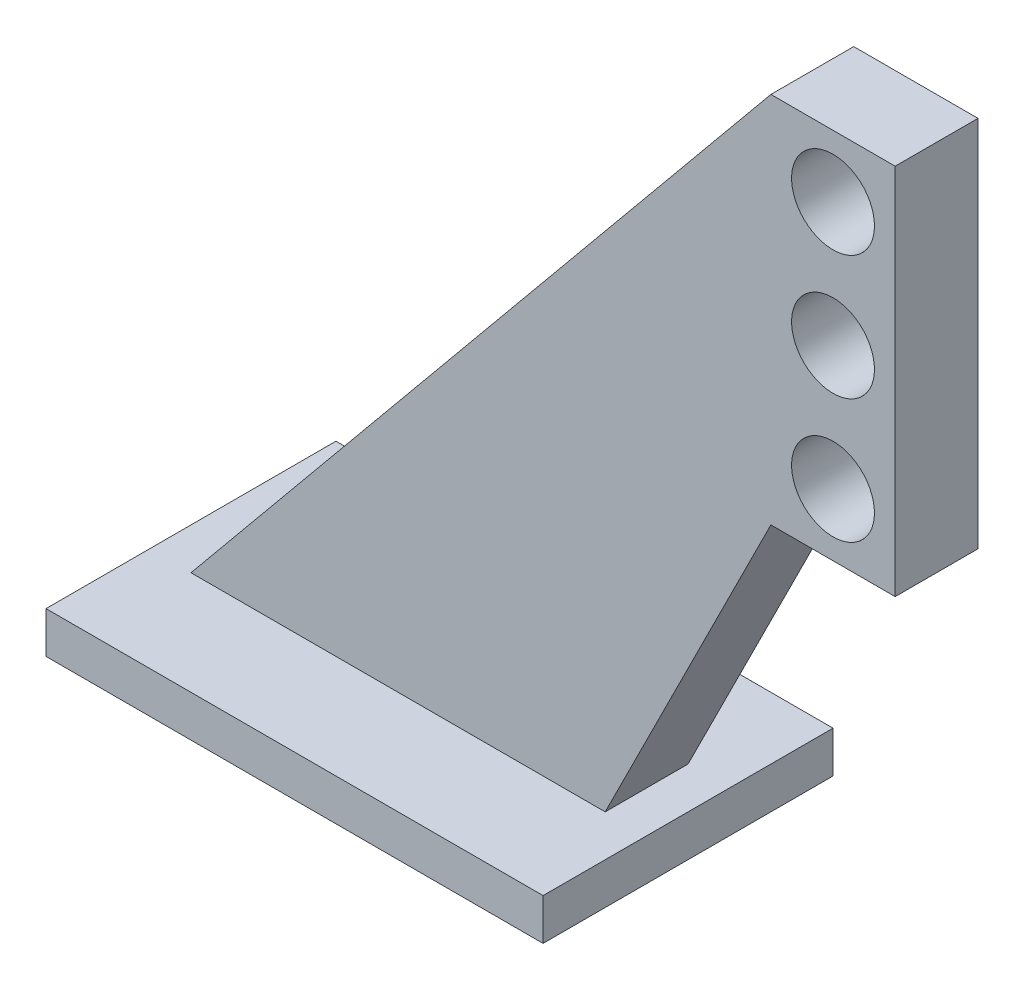
SolidWorks part; units mm, degrees
material "Zero density"
ref_plane "Piano frontale" through (0, 0, 0) normal (0, 0, 1) x (1, 0, 0)
ref_plane "Piano superiore" through (0, 0, 0) normal (0, 1, 0) x (1, 0, 0)
ref_plane "Piano destro" through (0, 0, 0) normal (1, 0, 0) x (0, 0, -1)
sketch "Schizzo1" plane through (0, 0, 0) normal (0, 0, 1) x (1, 0, 0)
  line L0 (0, 0) -> (10, 0)
  line L1 (10, 0) -> (14, 8)
  line L2 (14, 8) -> (17, 8)
  line L3 (17, 8) -> (17, 17)
  line L4 (17, 17) -> (14, 17)
  line L5 (14, 17) -> (0, 0)
  line L6 (15.5, 15.5) -> (15.5, 12.5) construction
  line L7 (15.5, 12.5) -> (15.5, 9.5) construction
  line L8 (15.5, 15.5) -> (17, 17) construction
  line L9 (15.5, 9.5) -> (17, 8) construction
  circle A0 centre (15.5, 15.5) radius 1
  circle A1 centre (15.5, 12.5) radius 1
  circle A2 centre (15.5, 9.5) radius 1
  point P14 (15.5, 17)
  dimension "D7" = 2
  dimension "D1" = 9
  dimension "D2" = 10
  dimension "D3" = 7
  dimension "D4" = 17
  dimension "D5" = 3
  dimension "D6" = 14
  dimension "D8" = 1.5
extrude "Estrusione-Estrusione1" add sketch "Schizzo1" along normal blind 2
sketch "Schizzo2" plane through (0, 0, 0) normal (0, -1, 0) x (1, 0, 0)
  line L0 (0, 2) -> (10, 0) construction
  line L1 (10, 0) -> (10, 2) construction
  line L2 (10, 2) -> (0, 0) construction
  line L4 (11, -2.5) -> (-1, -2.5)
  line L5 (11, -2.5) -> (11, 4.5)
  line L6 (11, 4.5) -> (-1, 4.5)
  line L7 (-1, -2.5) -> (-1, 4.5)
  line L8 (11, -2.5) -> (-1, 4.5) construction
  line L9 (11, 4.5) -> (-1, -2.5) construction
  point P4 (5, 1)
  dimension "D1" = 12
  dimension "D2" = 7
extrude "Estrusione-Estrusione2" add sketch "Schizzo2" along normal blind 1
